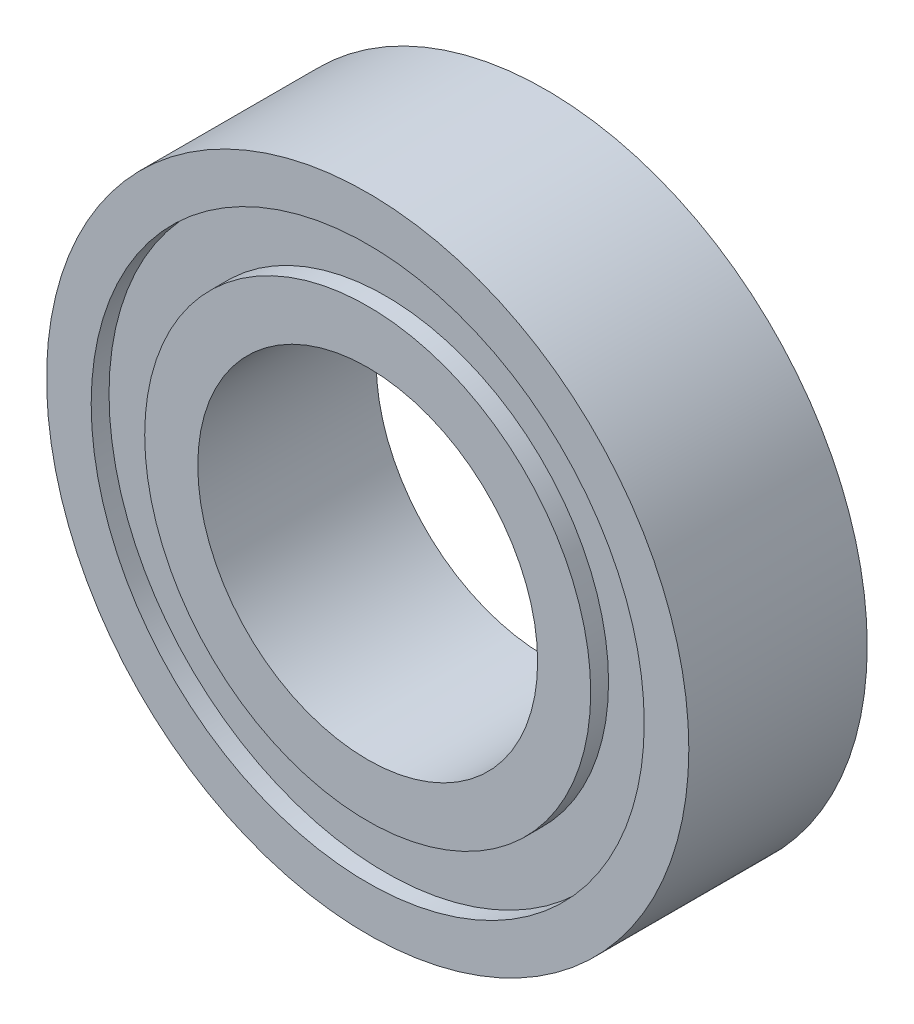
SolidWorks part; units mm, degrees
ref_plane "Plano frontal" through (0, 0, 0) normal (0, 0, 1) x (1, 0, 0)
ref_plane "Plano superior" through (0, 0, 0) normal (0, 1, 0) x (1, 0, 0)
ref_plane "Plano direito" through (0, 0, 0) normal (1, 0, 0) x (0, 0, -1)
sketch "Esboço1" plane through (0, 0, 0) normal (0, 0, 1) x (1, 0, 0)
  circle A0 centre (0, 0) radius 4.7625
  circle A1 centre (0, 0) radius 9
  dimension "D1" = 9.525
  dimension "D2" = 18
extrude "Ressalto-extrusão1" add sketch "Esboço1" along normal blind 5
sketch "Esboço2" plane through (0, 0, 0) normal (0, 0, -1) x (-1, 0, 0)
  circle A0 centre (0, 0) radius 6.25
  circle A1 centre (0, 0) radius 7.75
  dimension "D1" = 12.5
  dimension "D2" = 15.5
extrude "Corte-extrusão1" cut sketch "Esboço2" against normal blind 0.5
ref_plane "Plano1" through (0, 0, 2.5) normal (0, 0, 1) x (1, 0, 0)
mirror "Espelhar2" about plane through (0, 0, 2.5) normal (0, 0, 1) of "Corte-extrusão1"
